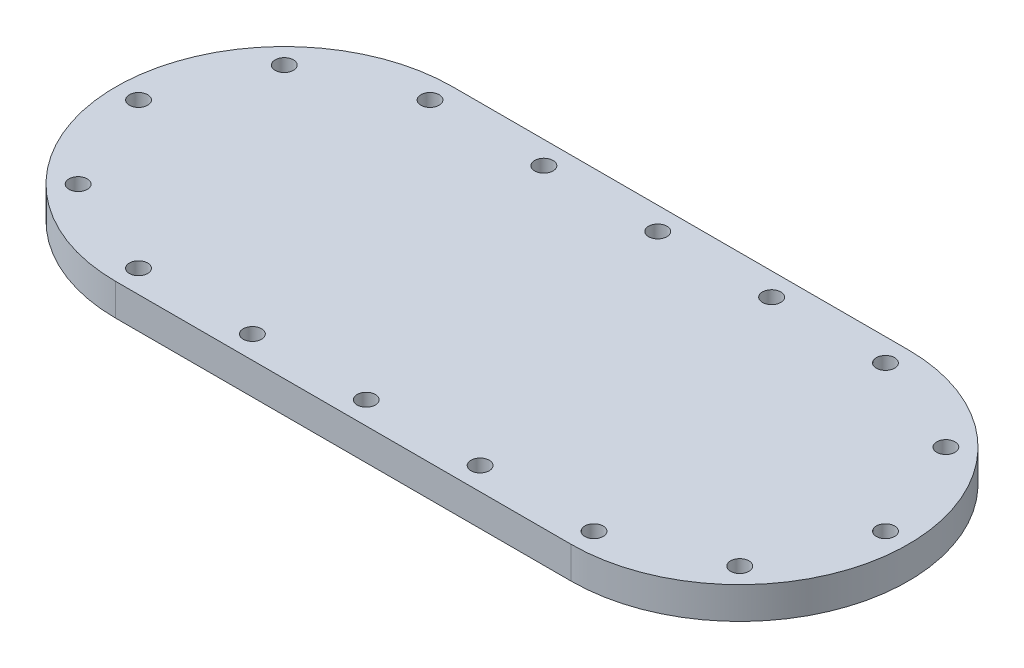
SolidWorks part; units mm, degrees
material "Acrylic (Medium-high impact)"
ref_plane "Front Plane" through (0, 0, 0) normal (0, 0, 1) x (1, 0, 0)
ref_plane "Top Plane" through (0, 0, 0) normal (0, 1, 0) x (1, 0, 0)
ref_plane "Right Plane" through (0, 0, 0) normal (1, 0, 0) x (0, 0, -1)
sketch "Sketch1" plane through (0, 0, 0) normal (0, 1, 0) x (1, 0, 0)
  line L0 (0, 46.99) -> (0, -46.99) construction
  line L3 (-63.5, 46.99) -> (63.5, 46.99)
  line L4 (-63.5, -46.99) -> (63.5, -46.99)
  line L5 (-63.5, 40.64) -> (63.5, 40.64) construction
  line L6 (-63.5, -40.64) -> (63.5, -40.64) construction
  arc A2 (63.5, -46.99) -> (63.5, 46.99) centre (63.5, 0) ccw
  arc A3 (-63.5, 46.99) -> (-63.5, -46.99) centre (-63.5, 0) ccw
  arc A4 (63.5, -40.64) -> (63.5, 40.64) centre (63.5, 0) ccw construction
  arc A5 (-63.5, 40.64) -> (-63.5, -40.64) centre (-63.5, 0) ccw construction
  circle A6 centre (-63.5, 40.64) radius 2.5527
  circle A7 centre (-31.75, 40.64) radius 2.5527
  circle A8 centre (0, 40.64) radius 2.5527
  circle A9 centre (31.75, 40.64) radius 2.5527
  circle A10 centre (63.5, 40.64) radius 2.5527
  circle A23 centre (92.2368, 28.7368) radius 2.5527
  circle A24 centre (104.14, 0) radius 2.5527
  circle A25 centre (92.2368, -28.7368) radius 2.5527
  circle A26 centre (63.5, -40.64) radius 2.5527
  circle A27 centre (-92.2368, 28.7368) radius 2.5527
  circle A28 centre (-104.14, 0) radius 2.5527
  circle A29 centre (-92.2368, -28.7368) radius 2.5527
  circle A30 centre (-63.5, -40.64) radius 2.5527
  circle A31 centre (31.75, -40.64) radius 2.5527
  circle A32 centre (0, -40.64) radius 2.5527
  circle A33 centre (-31.75, -40.64) radius 2.5527
  arc A34 (63.5, -40.64) -> (63.5, 40.64) centre (63.5, 0) ccw construction
  arc A35 (-63.5, 40.64) -> (-63.5, -40.64) centre (-63.5, 0) ccw construction
  point P42 (-63.5, 0)
  point P51 (-63.5, 0)
  point P53 (63.5, 0)
  dimension "D4" = 5
  dimension "1/4 - 20 bolt clearance" = 5.1054
  dimension "D5" = 5
  dimension "D1" = 127
  dimension "D2" = 93.98
  dimension "D3" = 6.35
  dimension "D7" = 4
  dimension "D6" = 5
extrude "Boss-Extrude1" add sketch "Sketch1" along normal blind 8.89
sketch "Sketch2" plane through (0, 0, 0) normal (0, -1, 0) x (1, 0, 0)
  line L0 (1.3877, 29.693) -> (65.9877, 29.693) construction
  line L1 (65.9877, 34.0618) -> (1.3877, 34.0618) construction
  line L2 (65.9877, -29.4382) -> (-63.2123, -29.4382) construction
  line L3 (-63.2123, -33.807) -> (65.9877, -33.807) construction
  line L4 (-63.2123, 29.693) -> (1.3877, 29.693) construction
  line L5 (1.3877, 34.0618) -> (-63.2123, 34.0618) construction
  line L6 (1.3877, 29.693) -> (65.9877, 29.693) construction
  line L7 (65.9877, 34.0618) -> (1.3877, 34.0618) construction
  line L8 (65.9877, -29.4382) -> (-63.2123, -29.4382) construction
  line L9 (-63.2123, -33.807) -> (65.9877, -33.807) construction
  line L10 (-63.2123, 29.693) -> (1.3877, 29.693) construction
  line L11 (1.3877, 34.0618) -> (-63.2123, 34.0618) construction
  arc A0 (65.9877, -29.4382) -> (65.9877, 29.693) centre (65.9877, 0.1274) ccw construction
  arc A1 (65.9877, -33.807) -> (65.9877, 34.0618) centre (65.9877, 0.1274) ccw construction
  arc A2 (-63.2123, 29.693) -> (-63.2123, -29.4382) centre (-63.2123, 0.1274) ccw construction
  arc A3 (-63.2123, 34.0618) -> (-63.2123, -33.807) centre (-63.2123, 0.1274) ccw construction
  arc A4 (65.9877, -29.4382) -> (65.9877, 29.693) centre (65.9877, 0.1274) ccw construction
  arc A5 (65.9877, -33.807) -> (65.9877, 34.0618) centre (65.9877, 0.1274) ccw construction
  arc A6 (-63.2123, 29.693) -> (-63.2123, -29.4382) centre (-63.2123, 0.1274) ccw construction
  arc A7 (-63.2123, 34.0618) -> (-63.2123, -33.807) centre (-63.2123, 0.1274) ccw construction
